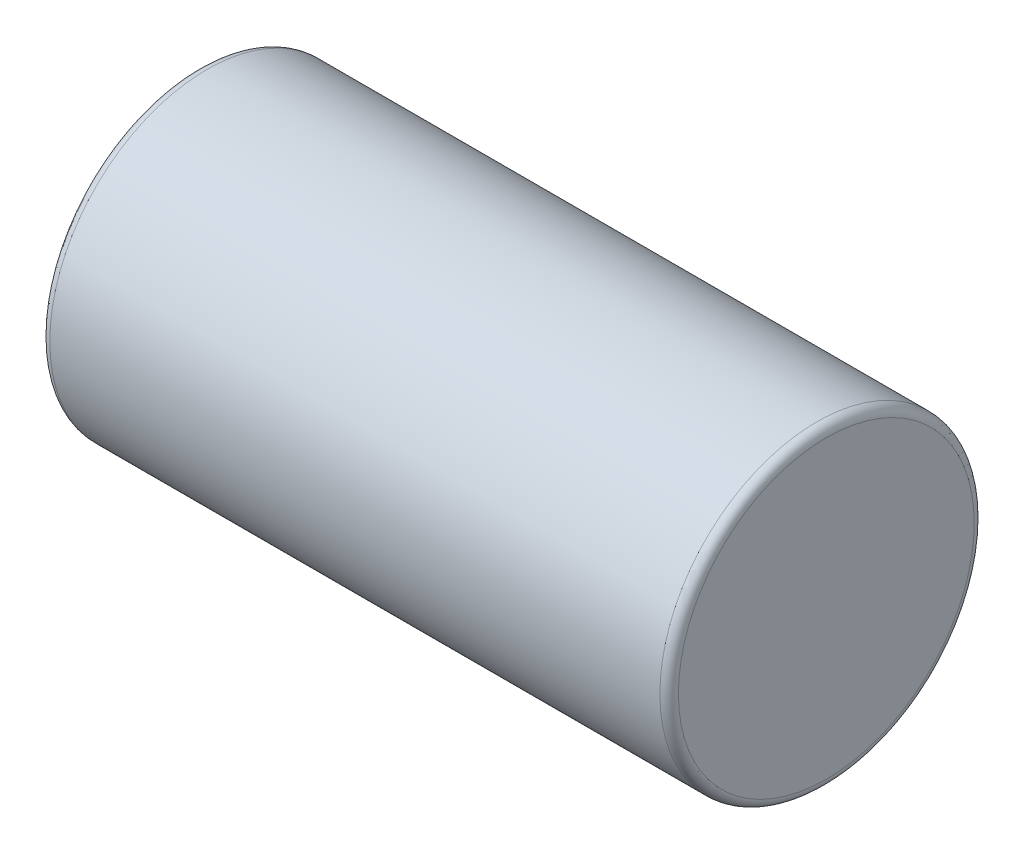
SolidWorks part; units mm, degrees
ref_plane "Спереди" through (0, 0, 0) normal (0, 0, 1) x (1, 0, 0)
ref_plane "Сверху" through (0, 0, 0) normal (0, 1, 0) x (1, 0, 0)
ref_plane "Справа" through (0, 0, 0) normal (1, 0, 0) x (0, 0, -1)
sketch "Эскиз2" plane through (0, 0, 0) normal (1, 0, 0) x (0, 0, -1)
  circle A0 centre (0, 0) radius 8.5
  dimension "D1" = 17
extrude "Бобышка-Вытянуть1" add sketch "Эскиз2" against normal blind 34
fillet "Скругление1" radius 0.5 2 edges at (0, 0, -8.5) (-34, 0, -8.5)
